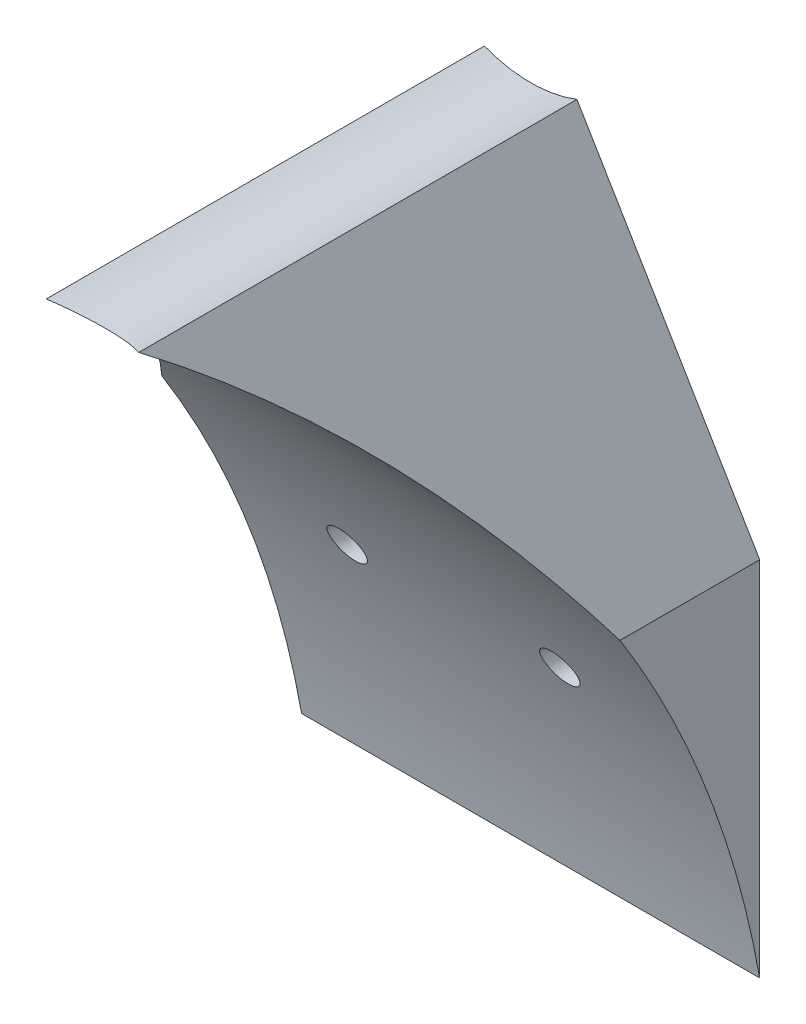
SolidWorks part; units mm, degrees
material "ABS"
ref_plane "Front Plane" through (0, 0, 0) normal (0, 0, 1) x (1, 0, 0)
ref_plane "Top Plane" through (0, 0, 0) normal (0, 1, 0) x (1, 0, 0)
ref_plane "Right Plane" through (0, 0, 0) normal (1, 0, 0) x (0, 0, -1)
sketch "Sketch1" plane through (0, 0, 0) normal (0, 0, 1) x (1, 0, 0)
  line L0 (0, 0) -> (0, -127) construction
  line L1 (0, 0) -> (38.9605, -65.4868) construction
  line L2 (0, 0) -> (-38.9605, -65.4868) construction
  line L3 (-38.9605, -65.4868) -> (-38.9605, -120.8763) construction
  line L5 (0, 0) -> (0, -127) construction
  line L6 (38.9605, -120.8763) -> (38.9605, -65.4868) construction
  line L7 (38.9605, -120.8763) -> (38.9605, -158.9763) construction
  line L8 (-50.8, -197.9368) -> (0, -197.9368) construction
  line L9 (-50.8, -193.1743) -> (0, -193.1743) construction
  line L10 (34.198, -120.8763) -> (34.198, -158.9763) construction
  line L11 (34.198, -120.8763) -> (34.198, -66.7963)
  line L12 (0, -9.3146) -> (34.198, -66.7963)
  line L13 (0, -9.3146) -> (-34.198, -66.7963)
  line L14 (-34.198, -66.7963) -> (-34.198, -120.8763)
  line L15 (-34.198, -120.8763) -> (-38.9605, -120.8763) construction
  line L16 (-50.8, -193.1743) -> (-50.8, -197.9368) construction
  line L17 (34.198, -120.8763) -> (-34.198, -120.8763)
  circle A0 centre (0, 0) radius 127 construction
  circle A1 centre (0, 0) radius 76.2 construction
  arc A2 (38.9605, -158.9763) -> (0, -197.9368) centre (0, -158.9763) cw construction
  arc A3 (34.198, -158.9763) -> (0, -193.1743) centre (0, -158.9763) cw construction
  point P2 (-15.875, -74.528)
  point P12 (0, 0)
  point P14 (15.875, -74.528)
  point P25 (0, -38.1)
  dimension "D2" = 152.4
  dimension "D6" = 4.7625
  dimension "D1" = 127
  dimension "D3" = 38.1
  dimension "D4" = 50.8
  dimension "D5" = 61.5
  dimension "D7" = 38.1
  dimension "D8" = 31.75
extrude "Boss-Extrude1" add sketch "Sketch1" along normal blind 76.2
sketch "Sketch2" plane through (0, 0, 0) normal (1, 0, 0) x (0, 0, -1)
  line L3 (-76.2, -120.8763) -> (0, -120.8763) construction
  line L4 (-76.2, -120.8763) -> (-76.2, -66.7963) construction
  line L6 (-76.2, -120.8763) -> (0, -120.8763)
  line L7 (-76.2, -120.8763) -> (-76.2, -66.7963)
  line L10 (-76.2, -66.7963) -> (-76.2, -9.3146) construction
  line L11 (-76.2, -22.225) -> (-76.2, -66.7963)
  line L12 (0, -66.7963) -> (0, -9.3146) construction
  line L13 (-76.2, -9.3146) -> (0, -9.3146) construction
  line L14 (-68.2625, -19.0675) -> (-68.2625, -9.3146)
  line L15 (-68.2625, -9.3146) -> (-76.2, -9.3146)
  line L16 (-76.2, -9.3146) -> (-76.2, -22.225)
  arc A0 (-68.2625, -19.0675) -> (0, -120.8763) centre (-150.0247, -147.6781) cw
  dimension "D1" = 68.2625
  dimension "D2" = 152.4
extrude "Cut-Extrude1" cut sketch "Sketch2" along normal up to surface (68.3961 mm away) from surface at -34.198 up to face at (34.198, -93.8363, 38.1) starting at face at (-34.198, -93.8363, 38.1)
sketch "Sketch5" plane through (0, 0, 0) normal (0, 0, 1) x (1, 0, 0)
  line L0 (0, -85.6549) -> (0, -3.1049) construction
  line L5 (36.9266, -65.173) -> (0, -3.1049)
  line L6 (0, -3.1049) -> (-36.9266, -65.173)
  line L7 (36.9266, -65.173) -> (0, -3.1049) construction
  line L8 (0, -3.1049) -> (-36.9266, -65.173) construction
  circle A0 centre (0, -3.1049) radius 82.55 construction
  circle A1 centre (0, -3.1049) radius 22.225 construction
  point P0 (0, -41.7129)
  point P4 (-15.875, -84.1141)
  point P5 (15.875, -84.1141)
  point P7 (1.8592, -3.1049)
  dimension "D1" = 3.175
  dimension "D3" = 165.1
  dimension "D4" = 44.45
  dimension "D2" = 31.75
  dimension "D5" = 38.608
hole_wizard "M5 Clearance Hole1" positions "Sketch7" profile "Sketch8" hole size "M5" standard "ANSI Metric" end condition through all
sketch "Sketch7" plane through (0, 0, 0) normal (0, 0, -1) x (-1, 0, 0)
  point P0 (-15.875, -84.1141)
  point P3 (15.875, -84.1141)
  point P6 (0, -41.7129)
sketch "Sketch8" plane through (15.875, -84.1141, 0) normal (1, 0, 0) x (0, 1, 0)
  line L0 (0, 0) -> (0, 68.2625)
  line L1 (0, 68.2625) -> (2.75, 68.2625)
  line L2 (2.75, 68.2625) -> (2.75, 0)
  line L5 (2.75, 0) -> (0, 0)
  line L11 (0, -6.35) -> (0, 107.95) construction
  dimension "Thru Hole Dia." = 5.5
  dimension "Thru Hole Depth" = 68.2625
sketch "Sketch10" plane through (0, 0, 0) normal (0, 0, -1) x (-1, 0, 0)
  circle A0 centre (0, -3.175) radius 19.05
  point P3 (0, 0)
  point P4 (0, 0)
  point P6 (0, -2.8525)
  point P7 (0, 0)
  point P9 (0, 0)
  point P10 (0, 0)
  point P12 (0, -3.1049)
  point P13 (0, -9.3146)
  point P14 (0, 0)
  point P16 (-5.778, 0)
  point P17 (0, 0)
  point P19 (0, 0)
  point P20 (0, -0.5413)
  dimension "D1" = 38.1
  dimension "D2" = 3.175
extrude "Cut-Extrude2" cut sketch "Sketch10" against normal up to next
sketch "Sketch11" plane through (0, 0, 0) normal (0, 0, -1) x (-1, 0, 0)
  line L0 (-31.023, -61.4596) -> (-31.023, -120.8763)
  line L1 (-34.198, -66.7963) -> (-6.9092, -20.9279) construction
  line L2 (34.198, -120.8763) -> (-34.198, -120.8763) construction
  line L3 (31.023, -61.4596) -> (31.023, -120.8763)
  line L4 (6.9092, -20.9279) -> (34.198, -66.7963) construction
  line L5 (31.023, -120.8763) -> (34.198, -120.8763)
  line L10 (34.198, -66.7963) -> (6.9092, -20.9279)
  line L11 (-6.9092, -20.9279) -> (-34.198, -66.7963)
  line L12 (-34.198, -66.7963) -> (-34.198, -120.8763)
  line L13 (-34.198, -120.8763) -> (34.198, -120.8763)
  line L14 (34.198, -120.8763) -> (34.198, -66.7963)
  line L15 (34.198, -66.7963) -> (31.023, -61.4596)
  line L16 (-31.023, -61.4596) -> (-34.198, -66.7963)
  line L17 (-34.198, -66.7963) -> (-34.198, -120.8763)
  line L18 (-34.198, -120.8763) -> (-31.023, -120.8763)
  line L19 (34.198, -120.8763) -> (34.198, -66.7963)
  arc A1 (-6.9092, -20.9279) -> (6.9092, -20.9279) centre (0, -3.175) ccw
  dimension "D2" = 3.175
  dimension "D3" = 3.175
  dimension "D1" = 0
